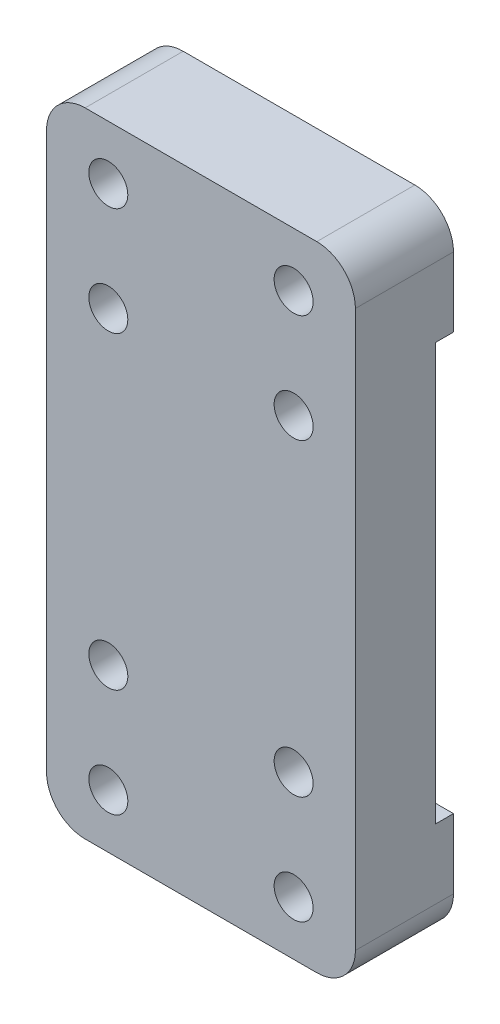
SolidWorks part; units mm, degrees
ref_plane "Front Plane" through (0, 0, 0) normal (0, 0, 1) x (1, 0, 0)
ref_plane "Top Plane" through (0, 0, 0) normal (0, 1, 0) x (1, 0, 0)
ref_plane "Right Plane" through (0, 0, 0) normal (1, 0, 0) x (0, 0, -1)
sketch "Sketch1" plane through (0, 0, 0) normal (0, 0, 1) x (1, 0, 0)
  line L1 (-20, -41) -> (20, -41)
  line L2 (-20, -41) -> (-20, 41)
  line L3 (-20, 41) -> (20, 41)
  line L4 (20, -41) -> (20, 41)
  line L5 (0, 41) -> (0, -41) construction
  line L6 (-20, 0) -> (20, 0) construction
  circle A0 centre (-12, 20) radius 2.525
  circle A1 centre (-12, 34) radius 2.525
  circle A2 centre (12, 34) radius 2.525
  circle A3 centre (12, 20) radius 2.525
  circle A4 centre (12, -20) radius 2.525
  circle A5 centre (12, -34) radius 2.525
  circle A6 centre (-12, -20) radius 2.525
  circle A7 centre (-12, -34) radius 2.525
  point P0 (0, 0)
  dimension "D1" = 20
  dimension "D2" = 34
  dimension "D3" = 5.05
  dimension "D5" = 7
  dimension "D6" = 20
  dimension "D7" = 12
extrude "Boss-Extrude1" add sketch "Sketch1" along normal blind 12.7
sketch "Sketch2" plane through (0, 0, 0) normal (0, 0, -1) x (-1, 0, 0)
  line L0 (20, 41) -> (20, -41) construction
  line L1 (-20, -27) -> (20, -27)
  line L2 (-20, -27) -> (-20, 27)
  line L3 (-20, 27) -> (20, 27)
  line L4 (20, -27) -> (20, 27)
  line L5 (0, 27) -> (0, -27) construction
  line L6 (-20, 0) -> (20, 0) construction
  point P0 (0, 0)
  dimension "D1" = 54
extrude "Cut-Extrude1" cut sketch "Sketch2" against normal blind 2.3
fillet "Fillet1" radius 5 4 edges at (-20, -41, 6.35) (20, -41, 6.35) (20, 41, 6.35) (-20, 41, 6.35)
